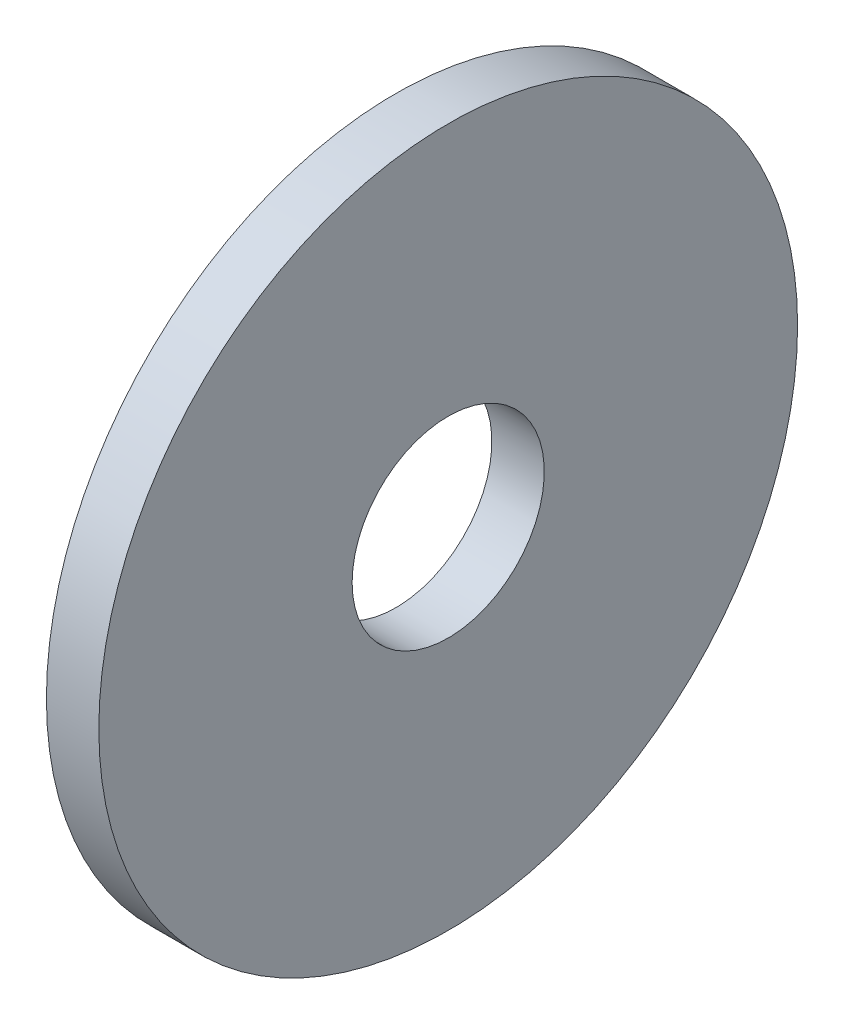
SolidWorks part; units mm, degrees
ref_plane "前基準面" through (0, 0, 0) normal (0, 0, 1) x (1, 0, 0)
ref_plane "上基準面" through (0, 0, 0) normal (0, 1, 0) x (1, 0, 0)
ref_plane "右基準面" through (0, 0, 0) normal (1, 0, 0) x (0, 0, -1)
ref_plane "平面1"
sketch "草圖1" plane through (0, 0, 0) normal (1, 0, 0) x (0, 1, 0)
  circle A0 centre (0, 0) radius 20
  circle A1 centre (0, 0) radius 5.5
  dimension "D1" = 11
  dimension "D2" = 40
extrude "本體" add sketch "草圖1" along normal blind 3 contours A0 A1
